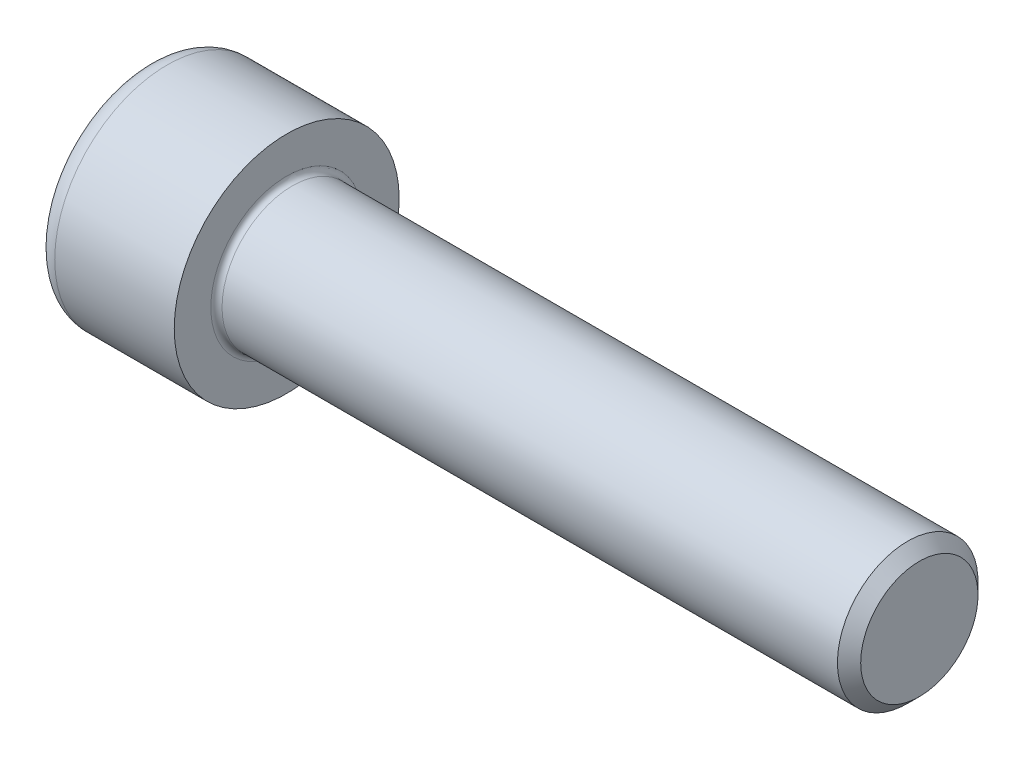
SolidWorks part; units mm, degrees
revolve "Base-Revolve" add sketch "BodySke"
sketch "BodySke" plane through (0, 0, 0) normal (0, 0, 1) x (1, 0, 0)
  line L0 (0, 0) -> (0, 8)
  line L1 (0, 8) -> (10, 8)
  line L2 (10, 8) -> (10, 5)
  line L3 (10, 5) -> (54.172, 5)
  line L4 (55, 4.172) -> (55, 0)
  line L5 (55, 0) -> (0, 0)
  line L6 (-31.75, 0) -> (127, 0) construction
  line L8 (55, 4.172) -> (54.172, 5)
  line L10 (55, -4.172) -> (54.172, -5) construction
  line L11 (11.5, 9.525) -> (11.5, 3.175) construction
  line L12 (10, 9.525) -> (10, 3.175) construction
  line L13 (-5, 9.525) -> (-5, 3.175) construction
  dimension "Body_ch_ang" = 45
  dimension "Advance" = 1.5
  dimension "Thread_length" = 60
cosmetic thread "ThreadCosmetic"
fillet "Fillet1" radius 0.4 1 edges at (10, 0, 5)
fillet "Fillet2" radius 1.5 1 edges at (0, 0, 8)
ref_plane "Plane1" through (0, 0, 0) normal (0, 0, 1) x (1, 0, 0)
ref_plane "Plane2" through (0, 0, 0) normal (0, 1, 0) x (1, 0, 0)
ref_plane "Plane3" through (0, 0, 0) normal (1, 0, 0) x (0, 0, -1)
other "Configuration Table"
sketch "Sketch2" plane through (0, 0, 0) normal (0, 0, 1) x (1, 0, 0)
  line L0 (0, 4.0575) -> (5, 4.0575)
  line L1 (5, 4.0575) -> (7.3426, 0)
  line L2 (-31.75, 0) -> (127, 0) construction
  line L3 (7.3426, 0) -> (0, 0)
  line L4 (0, 0) -> (0, 4.0575)
  line L6 (0, 0) -> (47.625, 0) construction
  dimension "D2" = 60
revolve "Hex-PreBroach" cut sketch "Sketch2" angle 360 about L6
sketch "Sketch3" plane through (0, 0, 0) normal (-1, 0, 0) x (0, 0.5, 0.866)
  line L0 (2.3426, 4.0575) -> (-2.3426, 4.0575)
  line L1 (-2.3426, 4.0575) -> (-4.6852, 0)
  line L2 (2.3426, 4.0575) -> (4.6852, 0)
  line L3 (2.3426, -4.0575) -> (4.6852, 0)
  line L4 (2.3426, -4.0575) -> (-2.3426, -4.0575)
  line L5 (-2.3426, -4.0575) -> (-4.6852, 0)
extrude "Hex" cut sketch "Sketch3" against normal blind 5
sketch "ThdSchSke" plane through (0, 0, 0) normal (0, 0, 1) x (1, 0, 0)
  line L0 (14.5, -4.172) -> (13.9202, -5)
  line L1 (14.5, -4.172) -> (15.0798, -5)
  line L2 (15.0798, -5) -> (15.0798, -6.25)
  line L3 (-3.175, 0) -> (5.1513, 0) construction
  line L4 (0, 6.5) -> (0, -6.5) construction
  line L5 (15.0798, -6.25) -> (13.9202, -6.25)
  line L6 (13.9202, -6.25) -> (13.9202, -5)
revolve "ThreadSchematic" [suppressed] cut sketch "ThdSchSke" angle 360 about L3
pattern_linear "ThdSchPat" [suppressed]
equation "\"D2@Sketch3\" = \"Hex_size@Sketch3\" / 2"
equation "\"D1@Sketch3\" = \"Hex_size@Sketch3\" / 2"
equation "\"D1@Sketch2\" = \"Hex_size@Sketch3\" / 2"
equation "\"Thread_minor@ThreadCosmetic\"  =  \"Minor_dia@BodySke\""
equation "\"Depth@Sketch2\" =  \"Key_eng@Hex\""
equation "\"Thread_length@ThreadCosmetic\" = ((sgn( (\"Length@BodySke\" - \"Advance@BodySke\" * 3.0) - \"Thread_nom@BodySke\" )-1)*( (\"Length@BodySke\" - \"Advance@BodySke\" * 3.0) - \"Thread_nom@BodySke\" ))/-2+ \"Thread_nom@BodySke\""
equation "\"Thread_minor@ThdSchSke\" = \"Minor_dia@BodySke\""
equation "\"Diameter@ThdSchSke\" = \"Diameter@BodySke\""
equation "\"Overcut@ThdSchSke\" = \"Diameter@BodySke\" * 1.25"
equation "\"Start@ThdSchSke\" = \"Head_ht@BodySke\" + \"Length@BodySke\" - \"Thread_length@ThreadCosmetic\"  '---Non-countersunk---"
equation "\"Num_threads@ThdSchPat\" = int( \"Thread_length@ThreadCosmetic\" / \"Advance@BodySke\" + 0.999 )  + 1"
equation "\"Advance@ThdSchPat\" = \"Thread_length@ThreadCosmetic\" /  (\"Num_threads@ThdSchPat\" - 1) 'relax it"
equation "\"Num_threads@ThdSchPat\" = \"Num_threads@ThdSchPat\" - sgn( \"Num_threads@ThdSchPat\" - 1) '---chamfered tips only---"
